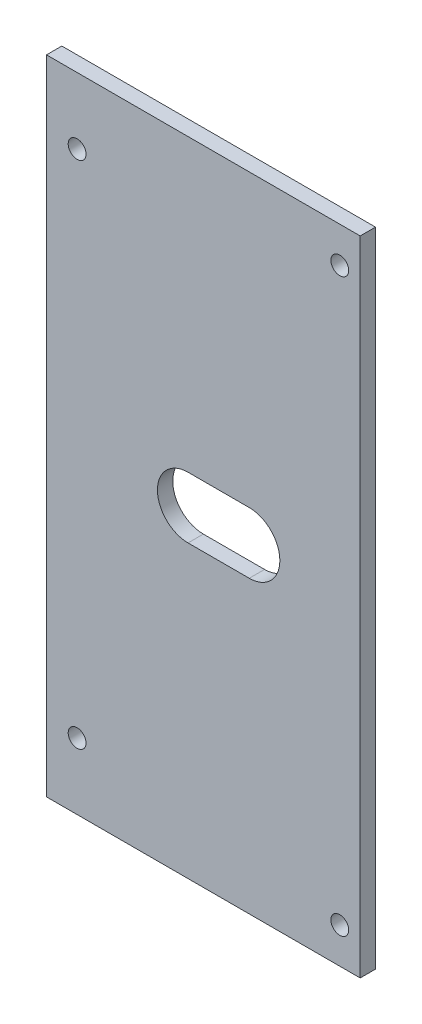
SolidWorks part; units mm, degrees
ref_plane "Front Plane" through (0, 0, 0) normal (0, 0, 1) x (1, 0, 0)
ref_plane "Top Plane" through (0, 0, 0) normal (0, 1, 0) x (1, 0, 0)
ref_plane "Right Plane" through (0, 0, 0) normal (1, 0, 0) x (0, 0, -1)
sketch "Sketch1" plane through (0, 0, 0) normal (0, 0, 1) x (1, 0, 0)
  line L0 (-83.8536, 0) -> (19.3888, 0) construction
  line L2 (-61.5, -63) -> (0, -63)
  line L3 (-61.5, -63) -> (-61.5, 63)
  line L4 (-61.5, 63) -> (0, 63)
  line L5 (0, -63) -> (0, 63)
  line L6 (-61.5, -63) -> (0, 63) construction
  line L7 (-61.5, 63) -> (0, -63) construction
  circle A0 centre (-4, 56) radius 1.75
  circle A1 centre (-55.5, 50) radius 1.75
  circle A2 centre (-4, -56) radius 1.75
  circle A3 centre (-55.5, -50) radius 1.75
  point P7 (-30.75, 0)
  dimension "D1" = 3.5
  dimension "D2" = 112
  dimension "D3" = 4
  dimension "D4" = 126
  dimension "D5" = 51.5
  dimension "D6" = 100
  dimension "D7" = 6
extrude "Boss-Extrude1" add sketch "Sketch1" along normal blind 3
sketch "Sketch2" plane through (0, 0, 3) normal (0, 0, 1) x (1, 0, 0)
  line L0 (-55.5, -50) -> (0, -50) construction
  line L1 (0, -63) -> (0, 63) construction
  line L2 (-27.75, -50) -> (-27.75, 63) construction
  line L3 (0, 63) -> (-61.5, 63) construction
  line L4 (0, 0) -> (-61.5, 0) construction
  line L5 (-61.5, 63) -> (-61.5, -63) construction
  line L6 (-33.75, 0) -> (-21.75, 0) construction
  line L7 (-33.75, 6) -> (-21.75, 6)
  line L8 (-33.75, -6) -> (-21.75, -6)
  arc A0 (-33.75, 6) -> (-33.75, -6) centre (-33.75, 0) ccw
  arc A1 (-21.75, -6) -> (-21.75, 6) centre (-21.75, 0) ccw
  point P16 (-27.75, 0)
  dimension "D1" = 12
  dimension "D2" = 12
extrude "Cut-Extrude1" cut sketch "Sketch2" against normal up to next
